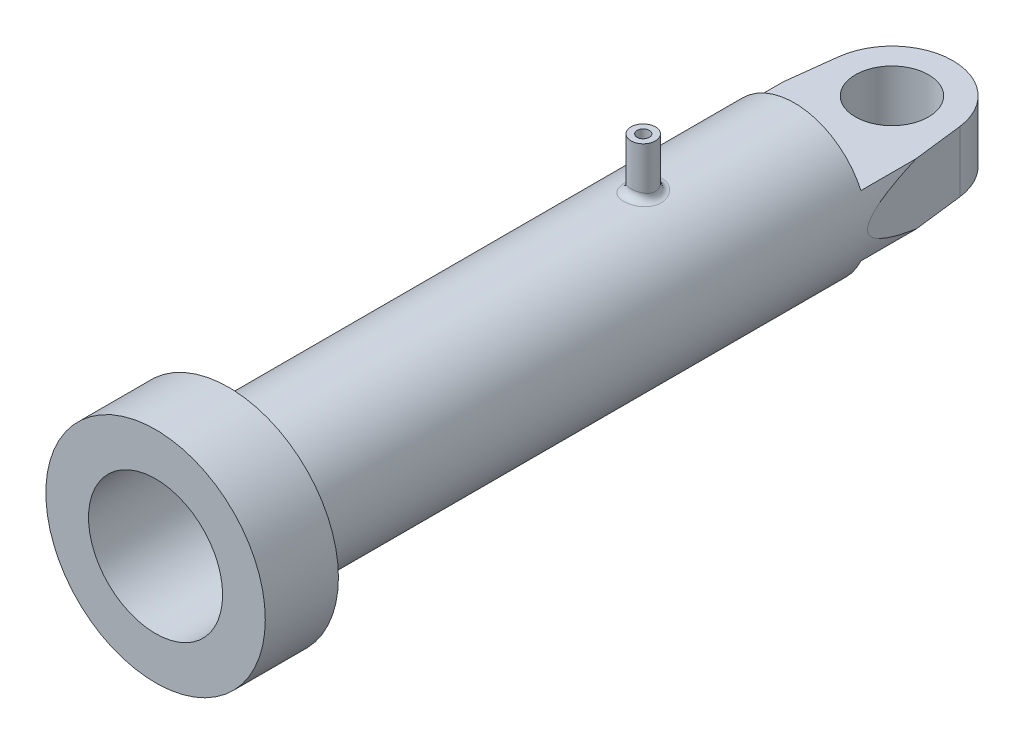
SolidWorks part; units mm, degrees
ref_plane "前基準面" through (0, 0, 0) normal (0, 0, 1) x (1, 0, 0)
ref_plane "上基準面" through (0, 0, 0) normal (0, 1, 0) x (1, 0, 0)
ref_plane "右基準面" through (0, 0, 0) normal (1, 0, 0) x (0, 0, -1)
sketch "草圖1" plane through (0, 0, 0) normal (0, 0, 1) x (1, 0, 0)
  circle A0 centre (0, 0) radius 4.5
  dimension "D1" = 9
extrude "填料-伸長1" add sketch "草圖1" against normal blind 3
sketch "草圖2" plane through (0, 0, 0) normal (0, 0, 1) x (1, 0, 0)
  circle A0 centre (0, 0) radius 3
  dimension "D1" = 6
extrude "填料-伸長2" add sketch "草圖2" against normal blind 26.2
sketch "草圖6" plane through (0, 0, 0) normal (0, 1, 0) x (1, 0, 0)
  line L0 (-3, 26.2) -> (-2.4821, 30.499)
  line L1 (0, 0) -> (0, 38.7893) construction
  line L2 (-4.5, 0) -> (4.5, 0) construction
  line L3 (3, 26.2) -> (-3, 26.2) construction
  line L4 (3, 26.2) -> (-3, 26.2)
  line L5 (3, 26.2) -> (2.4821, 30.499)
  arc A0 (-2.4821, 30.499) -> (2.4821, 30.499) centre (0, 30.2) cw
  circle A1 centre (0, 30.2) radius 1.5
  dimension "D1" = 2.5
  dimension "D3" = 3
  dimension "D2" = 4
extrude "填料-伸長3" add sketch "草圖6" along normal mid plane 2.5
sketch "草圖8" plane through (0, 0, -3) normal (0, 0, -1) x (-1, 0, 0)
  circle A0 centre (0, 0) radius 3 construction
  circle A1 centre (0, 0) radius 3
extrude "除料-伸長3" cut sketch "草圖8" along normal through all flip side to cut
sketch "草圖4" plane through (0, 0, 0) normal (0, 0, 1) x (1, 0, 0)
  circle A0 centre (0, 0) radius 2.75
  dimension "D1" = 5.5
extrude "除料-伸長1" cut sketch "草圖4" against normal blind 22.2
fillet "圓角2" radius 1 1 edges at (2.75, 0, -22.2)
sketch "草圖9" plane through (0, 0, 0) normal (0, 1, 0) x (1, 0, 0)
  line L0 (-2.75, 0) -> (2.75, 0) construction
  circle A0 centre (0, 20) radius 0.5
  dimension "D1" = 1
  dimension "D2" = 20
extrude "填料-伸長4" add sketch "草圖9" against normal up to next from offset 5
sketch "草圖10" plane through (0, 5, 0) normal (0, 1, 0) x (1, 0, 0)
  circle A0 centre (0, 20) radius 0.25
  dimension "D1" = 0.5
extrude "除料-伸長4" cut sketch "草圖10" against normal up to next
fillet "圓角3" radius 0.3 1 edges at (-0.1072, 2.9981, -20.4884)
